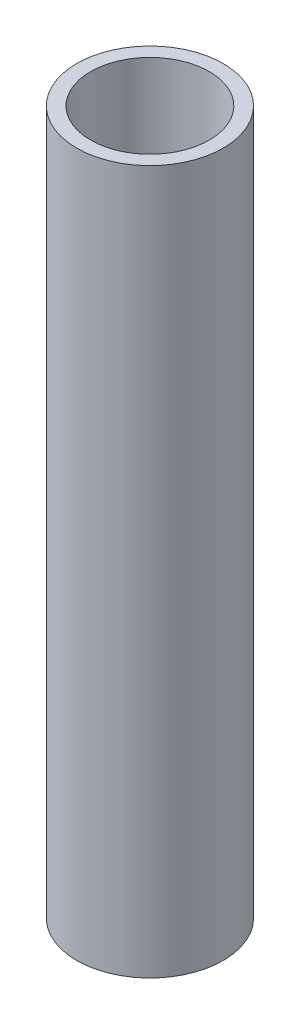
SolidWorks part; units mm, degrees
ref_plane "Front Plane" through (0, 0, 0) normal (0, 0, 1) x (1, 0, 0)
ref_plane "Top Plane" through (0, 0, 0) normal (0, 1, 0) x (1, 0, 0)
ref_plane "Right Plane" through (0, 0, 0) normal (1, 0, 0) x (0, 0, -1)
sketch "Sketch2" plane through (0, 0, 0) normal (0, 1, 0) x (1, 0, 0)
  circle A0 centre (0, 0) radius 0.5
  dimension "D1" = 1
extrude "Boss-Extrude1" add sketch "Sketch2" along normal blind 4.8
sketch "Sketch3" plane through (0, 0, 0) normal (0, 1, 0) x (1, 0, 0)
  circle A0 centre (0, 0) radius 0.405
  dimension "D1" = 0.81
extrude "Cut-Extrude2" cut sketch "Sketch3" against normal blind 10 and the other way through all
